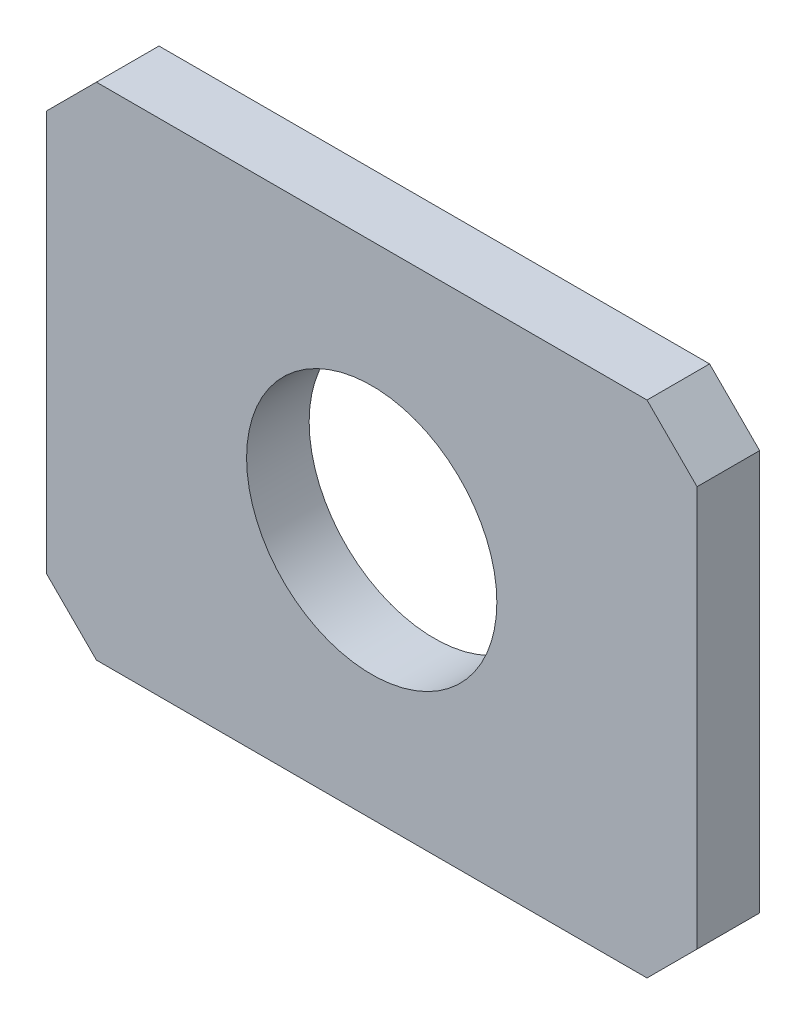
SolidWorks part; units mm, degrees
material "ASTM A36 Steel"
ref_plane "Front Plane" through (0, 0, 0) normal (0, 0, 1) x (1, 0, 0)
ref_plane "Top Plane" through (0, 0, 0) normal (0, 1, 0) x (1, 0, 0)
ref_plane "Right Plane" through (0, 0, 0) normal (1, 0, 0) x (0, 0, -1)
sketch "Sketch1" plane through (0, 0, 0) normal (0, 0, 1) x (1, 0, 0)
  line L1 (-78, -60) -> (78, -60)
  line L2 (-78, -60) -> (-78, 60)
  line L3 (-78, 60) -> (78, 60)
  line L4 (78, -60) -> (78, 60)
  line L5 (-78, -60) -> (78, 60) construction
  line L6 (-78, 60) -> (78, -60) construction
  point P0 (0, 0)
  dimension "D1" = 156
  dimension "D2" = 120
extrude "Boss-Extrude1" add sketch "Sketch1" along normal blind 15
sketch "Sketch2" plane through (0, 0, 15) normal (0, 0, 1) x (1, 0, 0)
  circle A0 centre (0, 0) radius 30
  dimension "D1" = 60
extrude "Cut-Extrude1" cut sketch "Sketch2" against normal blind 15
chamfer "Chamfer1" distance 12 angle 45 4 edges at (-78, -60, 7.5) (78, -60, 7.5) (78, 60, 7.5) (-78, 60, 7.5)
